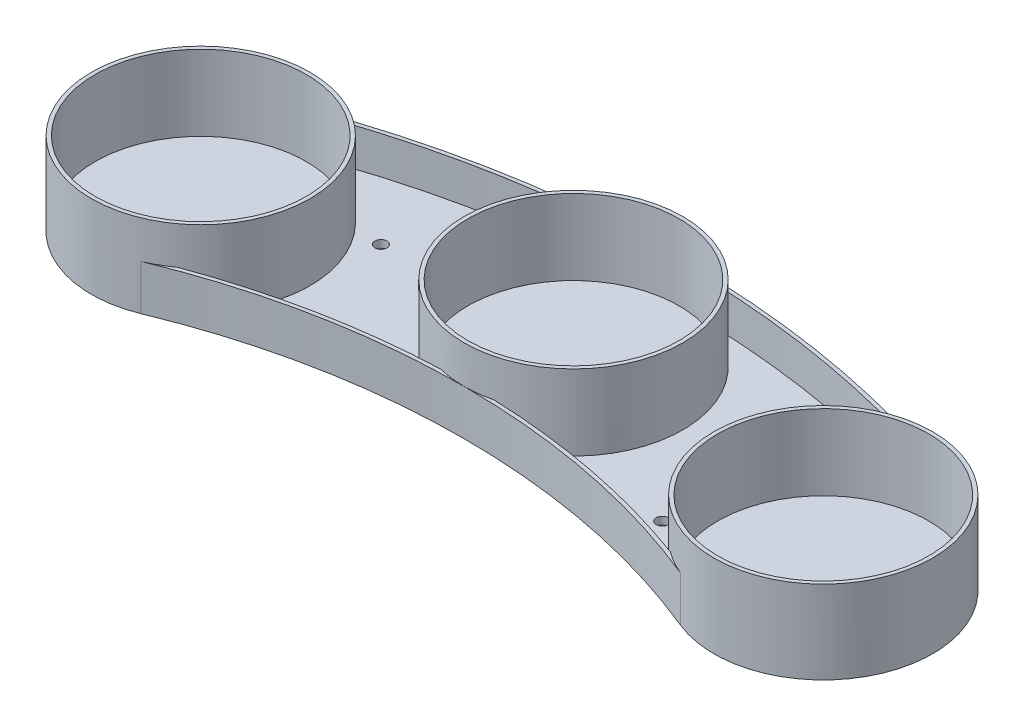
SolidWorks part; units mm, degrees
ref_plane "前视基准面" through (0, 0, 0) normal (0, 0, 1) x (1, 0, 0)
ref_plane "上视基准面" through (0, 0, 0) normal (0, 1, 0) x (1, 0, 0)
ref_plane "右视基准面" through (0, 0, 0) normal (1, 0, 0) x (0, 0, -1)
sketch "草图1" plane through (0, 0, 0) normal (0, 1, 0) x (1, 0, 0)
  line L0 (0, 0) -> (0, 454.1757) construction
  arc A0 (-93.5253, 227.528) -> (93.5253, 227.528) centre (0, 0) cw
  arc A4 (-93.5253, 227.528) -> (-71.4747, 173.8832) centre (-82.5, 200.7056) ccw
  arc A5 (-71.4747, 173.8832) -> (71.4747, 173.8832) centre (0, 0) cw
  arc A6 (93.5253, 227.528) -> (71.4747, 173.8832) centre (82.5, 200.7056) cw
  dimension "D1" = 246
  dimension "D2" = 58
  dimension "D3" = 165
extrude "凸台-拉伸1" add sketch "草图1" along normal blind 2
sketch "草图2" plane through (0, 2, 0) normal (0, 1, 0) x (1, 0, 0)
  line L0 (0, 246) -> (0, 188) construction
  circle A0 centre (-82.5, 200.7056) radius 29
  circle A1 centre (-82.5, 200.7056) radius 28
  arc A2 (93.5253, 227.528) -> (-93.5253, 227.528) centre (0, 0) ccw construction
  arc A3 (71.4747, 173.8832) -> (-71.4747, 173.8832) centre (0, 0) ccw construction
  circle A4 centre (0, 217) radius 28
  circle A5 centre (82.5, 200.7056) radius 28
  circle A6 centre (0, 217) radius 29
  circle A7 centre (82.5, 200.7056) radius 29
  dimension "D1" = 56
  dimension "D2" = 1
extrude "凸台-拉伸2" add sketch "草图2" along normal blind 20
sketch "草图3" plane through (0, 2, 0) normal (0, 1, 0) x (1, 0, 0)
  line L0 (-58.347, 238.9804) -> (0, 0) construction
  line L1 (0, 245) -> (0, 0) construction
  circle A1 centre (-53.6033, 219.5511) radius 1.6
  circle A2 centre (-47.1994, 193.3215) radius 1.6
  circle A3 centre (0, 217) radius 28 construction
  circle A4 centre (0, 217) radius 28 construction
  circle A5 centre (53.6033, 219.5511) radius 1.6
  circle A6 centre (47.1994, 193.3215) radius 1.6
  dimension "D1" = 3.2
  dimension "D2" = 20
  dimension "D3" = 27
  dimension "D4" = 94.3987
extrude "切除-拉伸1" cut sketch "草图3" against normal blind 10
sketch "草图4" plane through (0, 2, 0) normal (0, 1, 0) x (1, 0, 0)
  line L0 (93.1452, 226.6031) -> (93.5253, 227.528)
  line L1 (-93.1452, 226.6031) -> (-93.5253, 227.528)
  line L2 (71.4747, 173.8832) -> (71.8548, 174.8081)
  line L3 (-71.4747, 173.8832) -> (-71.8548, 174.8081)
  arc A0 (-93.5253, 227.528) -> (93.5253, 227.528) centre (0, 0) cw
  circle A1 centre (82.5, 200.7056) radius 29 construction
  arc A2 (-93.1452, 226.6031) -> (93.1452, 226.6031) centre (0, 0) cw
  circle A3 centre (-82.5, 200.7056) radius 28 construction
  circle A4 centre (82.5, 200.7056) radius 28 construction
  arc A5 (-71.4747, 173.8832) -> (71.4747, 173.8832) centre (0, 0) cw
  arc A6 (-71.8548, 174.8081) -> (71.8548, 174.8081) centre (0, 0) cw
extrude "凸台-拉伸3" add sketch "草图4" along normal blind 10
